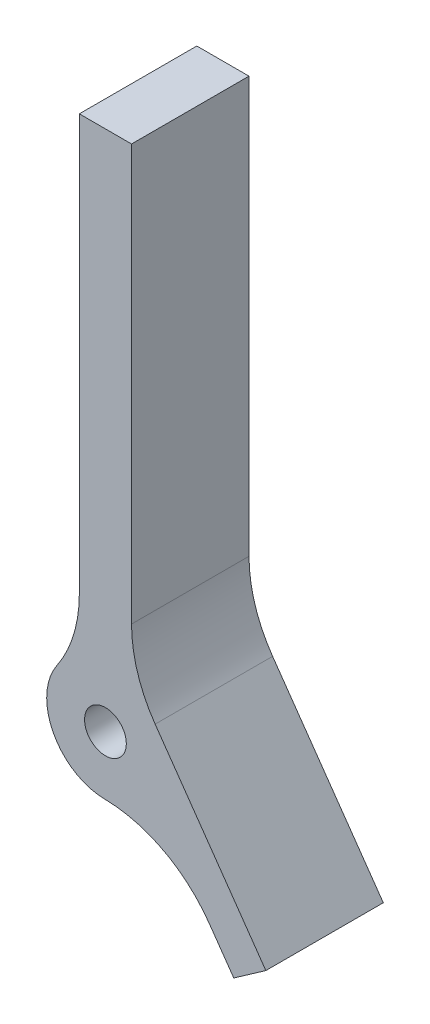
SolidWorks part; units mm, degrees
ref_plane "Front Plane" through (0, 0, 0) normal (0, 0, 1) x (1, 0, 0)
ref_plane "Top Plane" through (0, 0, 0) normal (0, 1, 0) x (1, 0, 0)
ref_plane "Right Plane" through (0, 0, 0) normal (1, 0, 0) x (0, 0, -1)
sketch "Sketch1" plane through (0, 0, 0) normal (0, 0, 1) x (1, 0, 0)
  line L0 (-3.8138, 22.5811) -> (4.7898, 10.2938)
  line L1 (4.7898, 10.2938) -> (2.3324, 8.5731)
  line L2 (2.3324, 8.5731) -> (-3.8378, 17.385)
  line L3 (-5.5, 24.0311) -> (-5.5, 60)
  line L4 (-5.5, 60) -> (-9.5, 60)
  line L5 (-9.5, 60) -> (-9.5, 24.0311)
  circle A0 centre (-7.5, 20) radius 1.6
  arc A1 (-3.8138, 22.5811) -> (-5.5, 24.0311) centre (-7.5, 20) ccw
  arc A2 (-9.5, 24.0311) -> (-3.8378, 17.385) centre (-7.5, 20) ccw
  point P3 (-3.8073, 17.3757)
  point P10 (-7.5, 60)
  dimension "D1" = 3.2
  dimension "D2" = 4.5
  dimension "D3" = 3
  dimension "D4" = 145
  dimension "D5" = 15
  dimension "D6" = 4
  dimension "D7" = 40
extrude "Boss-Extrude1" add sketch "Sketch1" along normal blind 9
fillet "Fillet1" radius 10 3 edges at (-3.8378, 17.385, 4.5) (-9.5, 24.0311, 4.5) (-5.5, 24.0311, 4.5)
